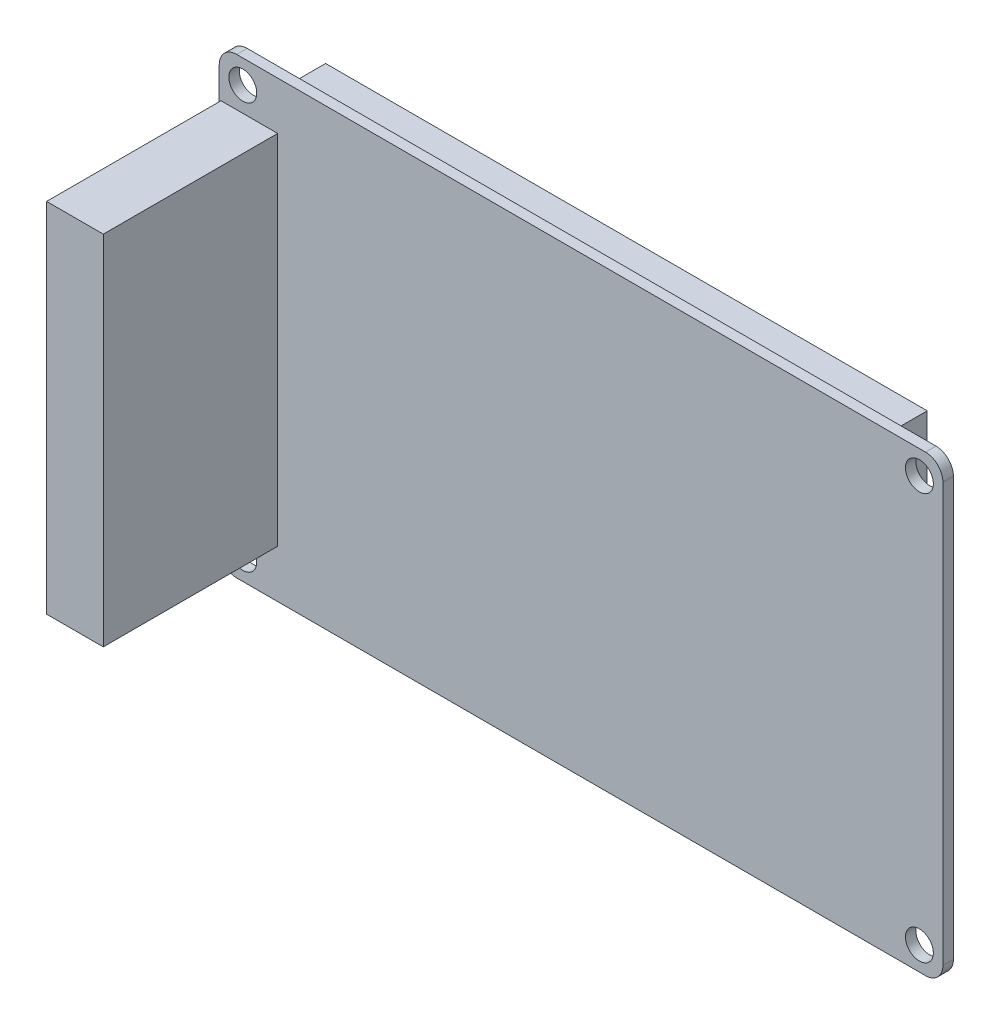
SolidWorks part; units mm, degrees
ref_plane "前视基准面" through (0, 0, 0) normal (0, 0, 1) x (1, 0, 0)
ref_plane "上视基准面" through (0, 0, 0) normal (0, 1, 0) x (1, 0, 0)
ref_plane "右视基准面" through (0, 0, 0) normal (1, 0, 0) x (0, 0, -1)
sketch "草图1" plane through (0, 0, 0) normal (0, 0, 1) x (1, 0, 0)
  line L1 (0, 0) -> (69, 0)
  line L2 (0, 0) -> (0, 50)
  line L3 (0, 50) -> (69, 50)
  line L4 (69, 0) -> (69, 50)
  dimension "D1" = 50
  dimension "D2" = 69
extrude "凸台-拉伸1" add sketch "草图1" along normal blind 4
sketch "草图2" plane through (0, 0, 4) normal (0, 0, 1) x (1, 0, 0)
  line L0 (0, 50) -> (0, 0) construction
  line L1 (-5, 51) -> (74, 51)
  line L2 (-7, 49) -> (-7, 1)
  line L3 (-5, -1) -> (74, -1)
  line L4 (76, 49) -> (76, 1)
  line L5 (69, 50) -> (0, 50) construction
  circle A0 centre (-4.3, 48.3) radius 1.6
  circle A1 centre (73.3, 48.3) radius 1.6
  circle A2 centre (-4.3, 1.7) radius 1.6
  circle A3 centre (73.3, 1.7) radius 1.6
  arc A4 (-7, 1) -> (-5, -1) centre (-5, 1) ccw
  arc A5 (74, -1) -> (76, 1) centre (74, 1) ccw
  arc A6 (74, 51) -> (76, 49) centre (74, 49) cw
  arc A7 (-5, 51) -> (-7, 49) centre (-5, 49) ccw
  point P14 (0, 25)
  point P17 (34.5, 50)
  point P18 (34.5, 51)
  point P19 (-7, 25)
  point P20 (0, 0)
  point P21 (0, 0)
  point P22 (0, 0)
  point P23 (0, 0)
  point P26 (-7, -1)
  point P31 (76, 51)
  point P34 (-7, 51)
  dimension "D7" = 3.2
  dimension "D8" = 2
  dimension "D1" = 77.6
  dimension "D2" = 83
  dimension "D3" = 52
  dimension "D4" = 46.6
  dimension "D5" = 23.3
  dimension "D6" = 38.8
extrude "凸台-拉伸2" add sketch "草图2" along normal blind 1.2
sketch "草图3" plane through (0, 0, 5.2) normal (0, 0, 1) x (1, 0, 0)
  line L1 (-6.8, 4.5) -> (-0.3, 4.5)
  line L2 (-6.8, 4.5) -> (-6.8, 45.5)
  line L3 (-6.8, 45.5) -> (-0.3, 45.5)
  line L4 (-0.3, 4.5) -> (-0.3, 45.5)
  line L5 (76, 1) -> (76, 49) construction
  line L6 (-7, 49) -> (-7, 1) construction
  point P8 (76, 25)
  point P9 (-0.3, 25)
  point P10 (0, 0)
  dimension "D1" = 41
  dimension "D2" = 6.5
  dimension "D3" = 0.2
extrude "凸台-拉伸3" add sketch "草图3" along normal blind 20
